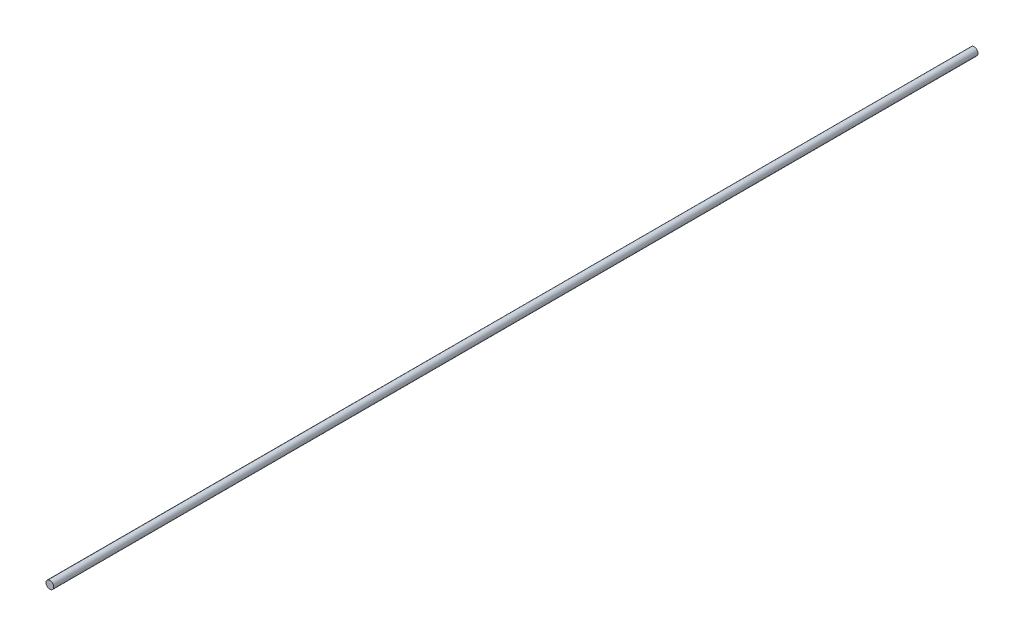
SolidWorks part; units mm, degrees
ref_plane "Front Plane" through (0, 0, 0) normal (0, 0, 1) x (1, 0, 0)
ref_plane "Top Plane" through (0, 0, 0) normal (0, 1, 0) x (1, 0, 0)
ref_plane "Right Plane" through (0, 0, 0) normal (1, 0, 0) x (0, 0, -1)
sketch "Sketch1" plane through (0, 0, 0) normal (0, 0, 1) x (1, 0, 0)
  circle A0 centre (0, 0) radius 1.5
  dimension "D1" = 3
extrude "Boss-Extrude1" add sketch "Sketch1" along normal blind 360
